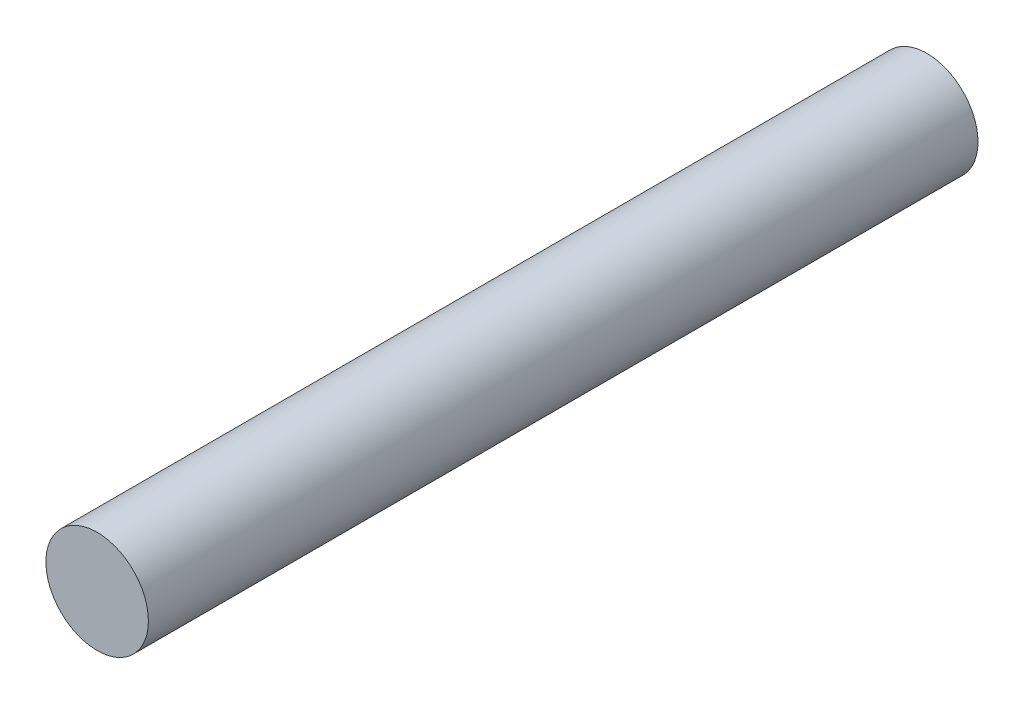
SolidWorks part; units mm, degrees
ref_plane "Alzado" through (0, 0, 0) normal (0, 0, 1) x (1, 0, 0)
ref_plane "Planta" through (0, 0, 0) normal (0, 1, 0) x (1, 0, 0)
ref_plane "Vista lateral" through (0, 0, 0) normal (1, 0, 0) x (0, 0, -1)
sketch "Croquis2" plane through (0, 0, 0) normal (0, 0, 1) x (1, 0, 0)
  circle A1 centre (0, 0) radius 5
  dimension "D2" = 10
extrude "Saliente-Extruir1" add sketch "Croquis2" along normal blind 80.95
sketch "Croquis3" plane through (0, 0, 80.95) normal (0, 0, 1) x (1, 0, 0)
  circle A0 centre (0, 0) radius 2.3813
  dimension "D1" = 4.7625
ref_plane "Plano1" through (0, 0, 34.125) normal (0, 0, 1) x (1, 0, 0)
